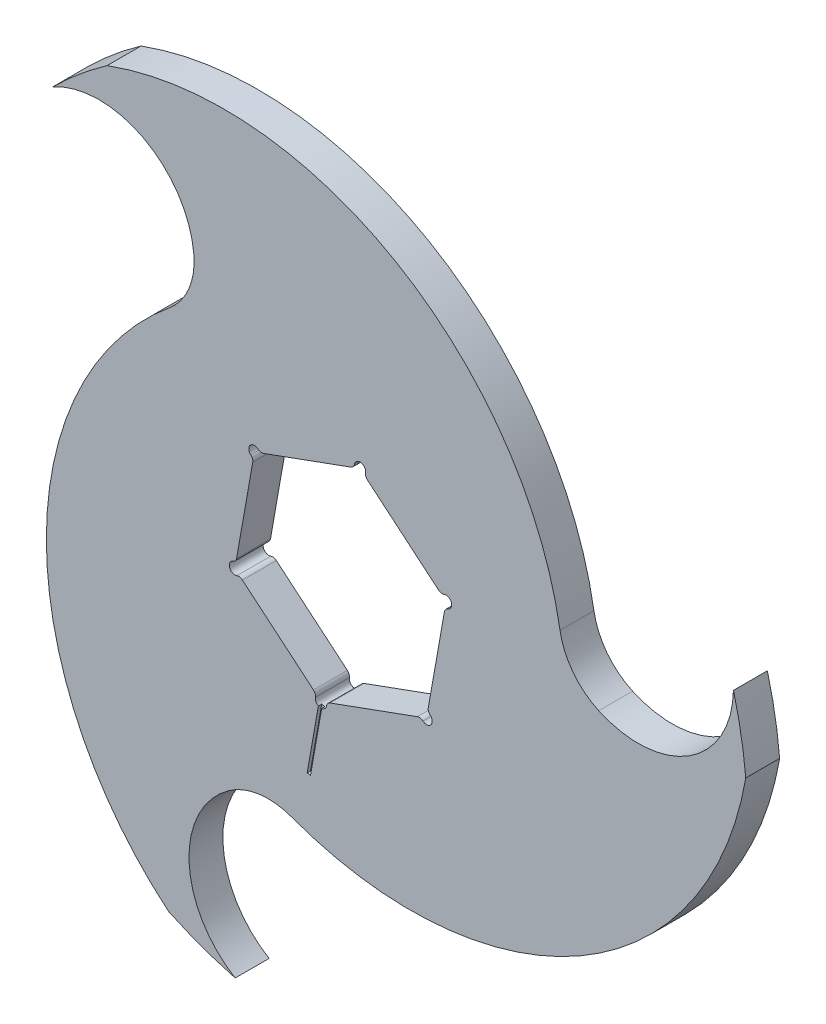
SolidWorks part; units mm, degrees
ref_plane "Front Plane" through (0, 0, 0) normal (0, 0, 1) x (1, 0, 0)
ref_plane "Top Plane" through (0, 0, 0) normal (0, 1, 0) x (1, 0, 0)
ref_plane "Right Plane" through (0, 0, 0) normal (1, 0, 0) x (0, 0, -1)
sketch "Sketch1" plane through (0, 0, 0) normal (0, 0, 1) x (1, 0, 0)
  line L19 (0, 0) -> (-42.4264, 42.4264) construction
  line L20 (0, 0) -> (0, 81.4053) construction
  line L21 (1.521, 15.8246) -> (-11.337, 11.1446)
  line L22 (-12.944, 9.2295) -> (-15.32, -4.2458)
  line L23 (-14.465, -6.595) -> (-3.983, -15.3904)
  line L24 (-1.521, -15.8246) -> (11.337, -11.1446)
  line L25 (12.944, -9.2295) -> (15.32, 4.2458)
  line L26 (14.465, 6.595) -> (3.983, 15.3904)
  line L27 (0, 0) -> (2.8773, 16.3182) construction
  arc A13 (-42.4264, 42.4264) -> (-22.6091, 24.8474) centre (-35.6099, 30.151) cw
  arc A14 (-10.2139, -32.0037) -> (59.7704, 5.2438) centre (10.2954, 13.8318) ccw
  arc A15 (59.7704, 5.2438) -> (57.9555, 15.5291) centre (0, 0) ccw
  arc A16 (57.9555, 15.5291) -> (32.823, 7.1564) centre (43.9165, 15.7636) cw
  arc A17 (32.823, 7.1564) -> (-34.4264, 49.1408) centre (-17.1264, 2.0002) ccw
  arc A18 (-34.4264, 49.1408) -> (-42.4264, 42.4264) centre (0, 0) ccw
  arc A19 (-22.6091, 24.8474) -> (-25.344, -54.3846) centre (6.8309, -15.832) ccw
  arc A20 (-25.344, -54.3846) -> (-15.5291, -57.9555) centre (0, 0) ccw
  arc A21 (-15.5291, -57.9555) -> (-10.2139, -32.0037) centre (-8.3066, -45.9146) cw
  circle A22 centre (0, 0) radius 14.35 construction
  arc A23 (3.698, 16.1735) -> (2.0567, 16.4629) centre (2.8773, 16.3182) ccw
  arc A24 (2.0567, 16.4629) -> (1.521, 15.8246) centre (1.236, 16.6076) cw
  arc A25 (3.983, 15.3904) -> (3.698, 16.1735) centre (4.5187, 16.0288) cw
  arc A26 (15.8557, 4.8842) -> (15.2856, 6.4503) centre (15.5707, 5.6673) ccw
  arc A27 (15.2856, 6.4503) -> (14.465, 6.595) centre (15.0006, 7.2334) cw
  arc A28 (15.32, 4.2458) -> (15.8557, 4.8842) centre (16.1407, 4.1011) cw
  arc A29 (12.1577, -11.2893) -> (13.229, -10.0126) centre (12.6933, -10.651) ccw
  arc A30 (13.229, -10.0126) -> (12.944, -9.2295) centre (13.7646, -9.3742) cw
  arc A31 (11.337, -11.1446) -> (12.1577, -11.2893) centre (11.622, -11.9277) cw
  arc A32 (-3.698, -16.1735) -> (-2.0567, -16.4629) centre (-2.8773, -16.3182) ccw
  arc A33 (-2.0567, -16.4629) -> (-1.521, -15.8246) centre (-1.236, -16.6076) cw
  arc A34 (-3.983, -15.3904) -> (-3.698, -16.1735) centre (-4.5187, -16.0288) cw
  arc A35 (-15.8557, -4.8842) -> (-15.2856, -6.4503) centre (-15.5707, -5.6673) ccw
  arc A36 (-15.2856, -6.4503) -> (-14.465, -6.595) centre (-15.0006, -7.2334) cw
  arc A37 (-15.32, -4.2458) -> (-15.8557, -4.8842) centre (-16.1407, -4.1011) cw
  arc A38 (-12.1577, 11.2893) -> (-13.229, 10.0126) centre (-12.6933, 10.651) ccw
  arc A39 (-13.229, 10.0126) -> (-12.944, 9.2295) centre (-13.7646, 9.3742) cw
  arc A40 (-11.337, 11.1446) -> (-12.1577, 11.2893) centre (-11.622, 11.9277) cw
  point P20 (0, 0)
  point P27 (0, 0)
  point P72 (0, 0)
  dimension "D5" = 0.8333
  dimension "D1" = 10
  dimension "D2" = 28.7
  dimension "D3" = 1.6667
  dimension "D4" = 0.8333
  dimension "D6" = 6
extrude "Boss-Extrude1" add sketch "Sketch1" along normal mid plane 5
fillet "Fillet1" radius 10 3 edges at (-10.2139, -32.0037, 0) (-22.6091, 24.8474, 0) (32.823, 7.1564, 0)
sketch "Sketch2" plane through (0, 0, 2.5) normal (0, 0, 1) x (1, 0, 0)
  line L0 (0, 0) -> (-3.022, -17.1389) construction
  line L1 (-3.022, -17.1389) -> (-2.9352, -16.6465) construction
  line L2 (-3.1814, -16.6031) -> (-2.689, -16.6899)
  line L3 (-3.1814, -16.6031) -> (-4.9179, -26.4512)
  line L4 (-2.689, -16.6899) -> (-4.4255, -26.538)
  line L5 (-4.9179, -26.4512) -> (-4.4255, -26.538)
  arc A0 (-3.698, -16.1735) -> (-2.0567, -16.4629) centre (-2.8773, -16.3182) ccw construction
  point P10 (-2.9352, -16.6465)
  dimension "D1" = 0.5
  dimension "D2" = 0.5
  dimension "D3" = 10
extrude "Cut-Extrude1" cut sketch "Sketch2" against normal blind 0.5
